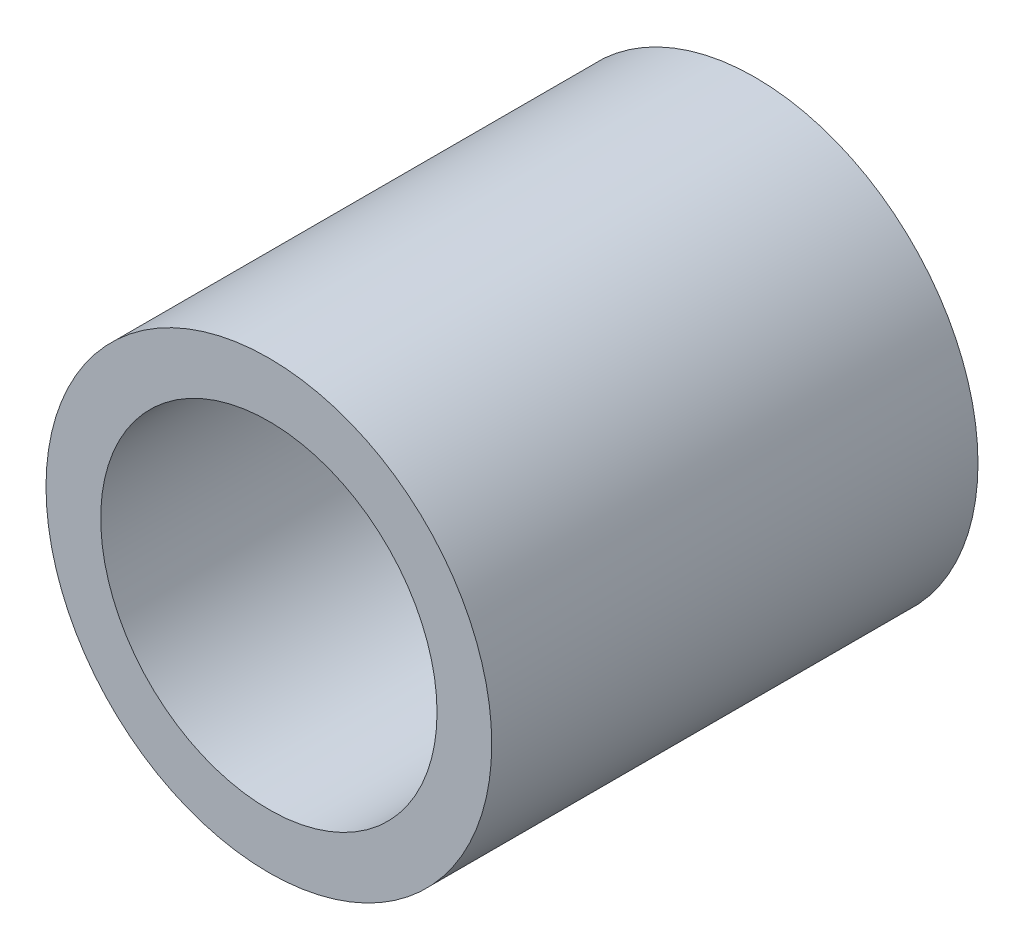
SolidWorks part; units mm, degrees
ref_plane "Front Plane" through (0, 0, 0) normal (0, 0, 1) x (1, 0, 0)
ref_plane "Top Plane" through (0, 0, 0) normal (0, 1, 0) x (1, 0, 0)
ref_plane "Right Plane" through (0, 0, 0) normal (1, 0, 0) x (0, 0, -1)
sketch "Sketch1" plane through (0, 0, 0) normal (0, 0, 1) x (1, 0, 0)
  circle A0 centre (0, 0) radius 4.15
  circle A1 centre (0, 0) radius 5.5
  dimension "D1" = 11
  dimension "D2" = 8.3
extrude "Boss-Extrude1" add sketch "Sketch1" along normal blind 12
